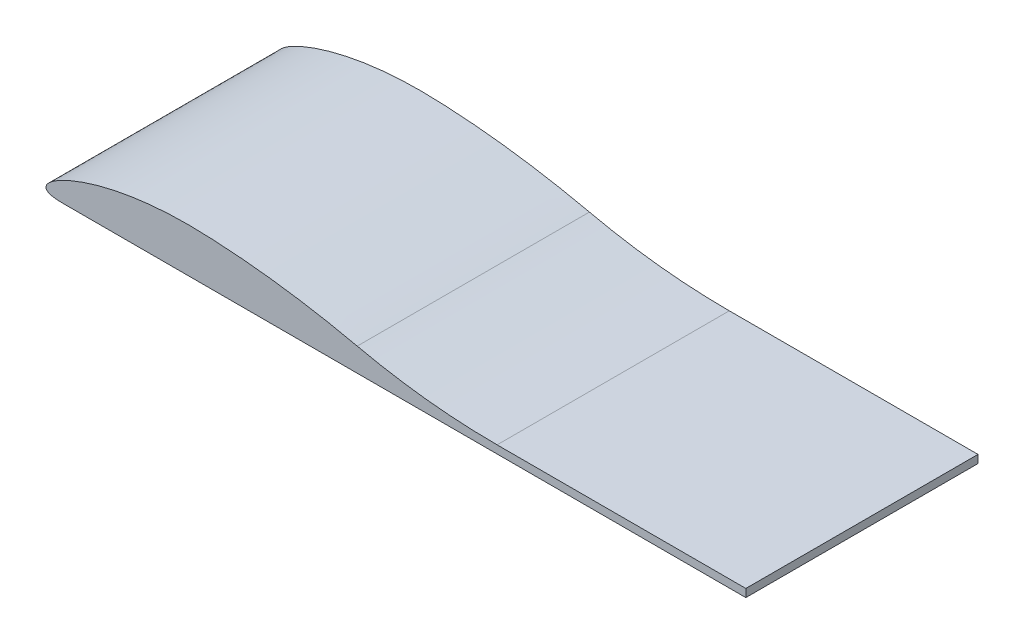
SolidWorks part; units mm, degrees
ref_plane "Front Plane" through (0, 0, 0) normal (0, 0, 1) x (1, 0, 0)
ref_plane "Top Plane" through (0, 0, 0) normal (0, 1, 0) x (1, 0, 0)
ref_plane "Right Plane" through (0, 0, 0) normal (1, 0, 0) x (0, 0, -1)
curve "Curve1"
  spline degree 3 poles (302.9843, 0.2066, 0) (305.2463, -0.0888, 0) (303.0423, 0.5058, 0) (301.2607, 1.1313, 0) (296.8595, 2.4314, 0) (291.4283, 4.0595, 0) (284.2715, 6.1062, 0) (275.7591, 8.441, 0) (265.8676, 11.0139, 0) (254.7283, 13.724, 0) (242.4522, 16.5013, 0) (229.1619, 19.2495, 0) (215.0022, 21.8919, 0) (200.1221, 24.3477, 0) (184.6818, 26.5449, 0) (168.8517, 28.4234, 0) (152.8082, 29.9307, 0) (136.7266, 31.0049, 0) (120.7051, 31.6889, 0) (104.9137, 31.6962, 0) (89.5649, 30.8862, 0) (74.9378, 29.3709, 0) (61.2207, 27.2233, 0) (48.5868, 24.554, 0) (37.1861, 21.5011, 0) (27.1553, 18.1971, 0) (18.5969, 14.8045, 0) (11.6064, 11.436, 0) (6.2054, 8.2632, 0) (2.4621, 5.3102, 0) (0.1728, 2.7181, 0) (-0.3667, -0.1067, 0) (1.6185, -2.1752, 0) (4.9031, -3.1118, 0) (9.5405, -3.659, 0) (15.6223, -3.6847, 0) (23.0877, -3.3095, 0) (31.8617, -2.5607, 0) (41.8437, -1.5362, 0) (52.932, -0.3245, 0) (65.0085, 0.9827, 0) (77.9641, 2.2775, 0) (91.674, 3.4466, 0) (106.0204, 4.4121, 0) (120.9553, 5.0518, 0) (136.3391, 5.4103, 0) (152.0077, 5.7293, 0) (167.7158, 5.8914, 0) (183.2867, 5.9078, 0) (198.553, 5.7595, 0) (213.3478, 5.4574, 0) (227.5084, 5.0134, 0) (240.8771, 4.4585, 0) (253.3023, 3.8196, 0) (264.6365, 3.1406, 0) (274.7593, 2.4517, 0) (283.5118, 1.8033, 0) (290.9024, 1.2074, 0) (296.5367, 0.7424, 0) (301.0977, 0.3102, 0) (302.9843, 0.2066, 0) (305.2463, -0.0888, 0) (303.0423, 0.5058, 0) knots -0.012269 -0.005489 -0.001366 0 0.001375 0.005484 0.012273 0.021682 0.033581 0.047831 0.064306 0.082777 0.103064 0.124929 0.148149 0.172445 0.197572 0.223269 0.249228 0.275186 0.300901 0.326463 0.351222 0.374906 0.39727 0.418072 0.43708 0.454093 0.46892 0.481392 0.491447 0.499024 0.504294 0.507922 0.51154 0.516781 0.524216 0.533992 0.546034 0.56022 0.576403 0.594371 0.613951 0.634917 0.657089 0.68023 0.704175 0.72909 0.754354 0.779668 0.80476 0.829359 0.853209 0.876041 0.897604 0.917662 0.93597 0.95231 0.966503 0.97835 0.987731 0.994511 0.998634 1 1.001375 1.005484 1.012273 periodic
sketch "Sketch1" plane through (0, 0, 0) normal (0, 0, 1) x (1, 0, 0)
  line L0 (304.8, 0) -> (304.8, -3.8991) construction
  line L1 (304.8, -3.8991) -> (0, -3.8991) construction
  line L2 (0, -3.8991) -> (0, 0) construction
  line L3 (304.8, 0) -> (304.8, 31.6609) construction
  line L4 (304.8, 31.6609) -> (0, 31.6609) construction
  line L5 (0, 31.6609) -> (0, 0) construction
  line L6 (13.1611, -3.6546) -> (558.8, -3.6546)
  line L7 (558.8, -3.6546) -> (558.8, 2.6954)
  line L8 (558.8, 2.6954) -> (295.9852, 2.6954)
  spline S0 degree 3 poles (302.9843, 0.2066) (305.2463, -0.0888) (303.0423, 0.5058) (301.2607, 1.1313) (296.8595, 2.4314) (291.4283, 4.0595) (284.2715, 6.1062) (275.7591, 8.441) (265.8676, 11.0139) (254.7283, 13.724) (242.4522, 16.5013) (229.1619, 19.2495) (215.0022, 21.8919) (200.1221, 24.3477) (184.6818, 26.5449) (168.8517, 28.4234) (152.8082, 29.9307) (136.7266, 31.0049) (120.7051, 31.6889) (104.9137, 31.6962) (89.5649, 30.8862) (74.9378, 29.3709) (61.2207, 27.2233) (48.5868, 24.554) (37.1861, 21.5011) (27.1553, 18.1971) (18.5969, 14.8045) (11.6064, 11.436) (6.2054, 8.2632) (2.4621, 5.3102) (0.1728, 2.7181) (-0.3667, -0.1067) (1.6185, -2.1752) (4.9031, -3.1118) (9.5405, -3.659) (15.6223, -3.6847) (23.0877, -3.3095) (31.8617, -2.5607) (41.8437, -1.5362) (52.932, -0.3245) (65.0085, 0.9827) (77.9641, 2.2775) (91.674, 3.4466) (106.0204, 4.4121) (120.9553, 5.0518) (136.3391, 5.4103) (152.0077, 5.7293) (167.7158, 5.8914) (183.2867, 5.9078) (198.553, 5.7595) (213.3478, 5.4574) (227.5084, 5.0134) (240.8771, 4.4585) (253.3023, 3.8196) (264.6365, 3.1406) (274.7593, 2.4517) (283.5118, 1.8033) (290.9024, 1.2074) (296.5367, 0.7424) (301.0977, 0.3102) (302.9843, 0.2066) (305.2463, -0.0888) (303.0423, 0.5058) knots -0.012269 -0.005489 -0.001366 0 0.001375 0.005484 0.012273 0.021682 0.033581 0.047831 0.064306 0.082777 0.103064 0.124929 0.148149 0.172445 0.197572 0.223269 0.249228 0.275186 0.300901 0.326463 0.351222 0.374906 0.39727 0.418072 0.43708 0.454093 0.46892 0.481392 0.491447 0.499024 0.504294 0.507922 0.51154 0.516781 0.524216 0.533992 0.546034 0.56022 0.576403 0.594371 0.613951 0.634917 0.657089 0.68023 0.704175 0.72909 0.754354 0.779668 0.80476 0.829359 0.853209 0.876041 0.897604 0.917662 0.93597 0.95231 0.966503 0.97835 0.987731 0.994511 0.998634 1 1.001375 1.005484 1.012273 only from (304.8, 0) to (304.8, 0) construction
  spline S1 degree 3 poles (302.9843, 0.2066) (305.2463, -0.0888) (303.0423, 0.5058) (301.2607, 1.1313) (296.8595, 2.4314) (291.4283, 4.0595) (284.2715, 6.1062) (275.7591, 8.441) (265.8676, 11.0139) (254.7283, 13.724) (242.4522, 16.5013) (229.1619, 19.2495) (215.0022, 21.8919) (200.1221, 24.3477) (184.6818, 26.5449) (168.8517, 28.4234) (152.8082, 29.9307) (136.7266, 31.0049) (120.7051, 31.6889) (104.9137, 31.6962) (89.5649, 30.8862) (74.9378, 29.3709) (61.2207, 27.2233) (48.5868, 24.554) (37.1861, 21.5011) (27.1553, 18.1971) (18.5969, 14.8045) (11.6064, 11.436) (6.2054, 8.2632) (2.4621, 5.3102) (0.1728, 2.7181) (-0.3667, -0.1067) (1.6185, -2.1752) (4.9031, -3.1118) (9.5405, -3.659) (15.6223, -3.6847) (23.0877, -3.3095) (31.8617, -2.5607) (41.8437, -1.5362) (52.932, -0.3245) (65.0085, 0.9827) (77.9641, 2.2775) (91.674, 3.4466) (106.0204, 4.4121) (120.9553, 5.0518) (136.3391, 5.4103) (152.0077, 5.7293) (167.7158, 5.8914) (183.2867, 5.9078) (198.553, 5.7595) (213.3478, 5.4574) (227.5084, 5.0134) (240.8771, 4.4585) (253.3023, 3.8196) (264.6365, 3.1406) (274.7593, 2.4517) (283.5118, 1.8033) (290.9024, 1.2074) (296.5367, 0.7424) (301.0977, 0.3102) (302.9843, 0.2066) (305.2463, -0.0888) (303.0423, 0.5058) knots -0.012269 -0.005489 -0.001366 0 0.001375 0.005484 0.012273 0.021682 0.033581 0.047831 0.064306 0.082777 0.103064 0.124929 0.148149 0.172445 0.197572 0.223269 0.249228 0.275186 0.300901 0.326463 0.351222 0.374906 0.39727 0.418072 0.43708 0.454093 0.46892 0.481392 0.491447 0.499024 0.504294 0.507922 0.51154 0.516781 0.524216 0.533992 0.546034 0.56022 0.576403 0.594371 0.613951 0.634917 0.657089 0.68023 0.704175 0.72909 0.754354 0.779668 0.80476 0.829359 0.853209 0.876041 0.897604 0.917662 0.93597 0.95231 0.966503 0.97835 0.987731 0.994511 0.998634 1 1.001375 1.005484 1.012273 only from (304.8, 0) to (304.8, 0)
  dimension "D1" = 35.56
  dimension "D2" = 558.8
  dimension "D3" = 6.35
extrude "Boss-Extrude1" add sketch "Sketch1" along normal blind 185.42 contours S1 L6 L7 L8 | S1
fillet "Fillet1" radius 508 1 edges at (295.9852, 2.6954, 92.71)
